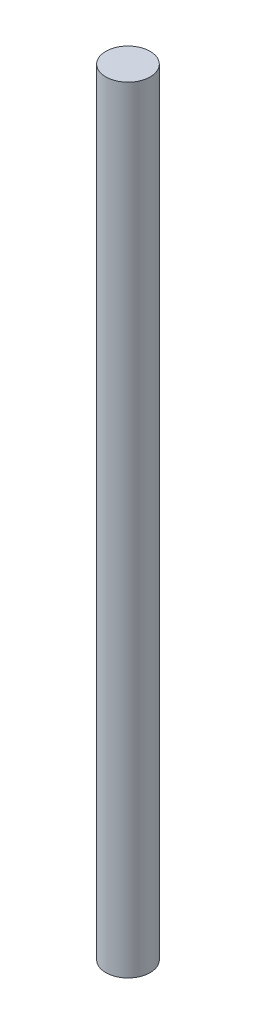
SolidWorks part; units mm, degrees
ref_plane "前视基准面" through (0, 0, 0) normal (0, 0, 1) x (1, 0, 0)
ref_plane "上视基准面" through (0, 0, 0) normal (0, 1, 0) x (1, 0, 0)
ref_plane "右视基准面" through (0, 0, 0) normal (1, 0, 0) x (0, 0, -1)
sketch "草图1" plane through (0, 0, 0) normal (0, 1, 0) x (1, 0, 0)
  circle A0 centre (0, 0) radius 1
  dimension "D1" = 2
extrude "凸台-拉伸1" add sketch "草图1" along normal blind 35
